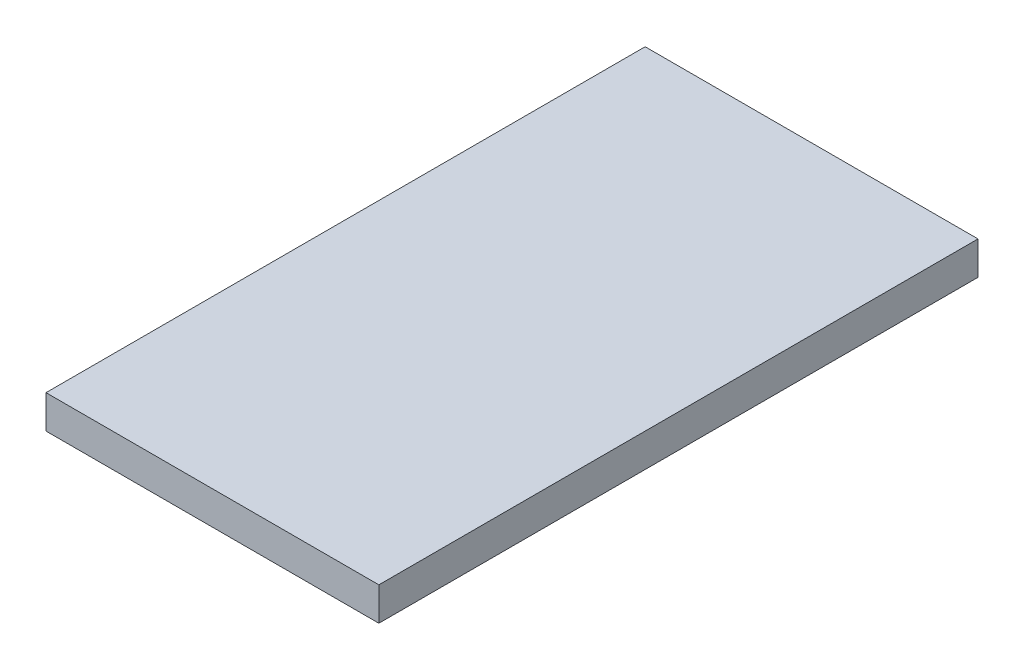
SolidWorks part; units mm, degrees
ref_plane "Front Plane" through (0, 0, 0) normal (0, 0, 1) x (1, 0, 0)
ref_plane "Top Plane" through (0, 0, 0) normal (0, 1, 0) x (1, 0, 0)
ref_plane "Right Plane" through (0, 0, 0) normal (1, 0, 0) x (0, 0, -1)
sketch "Sketch1" plane through (0, 0, 0) normal (0, 1, 0) x (1, 0, 0)
  line L1 (-50, -90) -> (50, -90)
  line L2 (-50, -90) -> (-50, 90)
  line L3 (-50, 90) -> (50, 90)
  line L4 (50, -90) -> (50, 90)
  line L5 (-50, -90) -> (50, 90) construction
  line L6 (-50, 90) -> (50, -90) construction
  point P0 (0, 0)
  dimension "D1" = 100
  dimension "D2" = 180
extrude "Boss-Extrude1" add sketch "Sketch1" along normal blind 10
